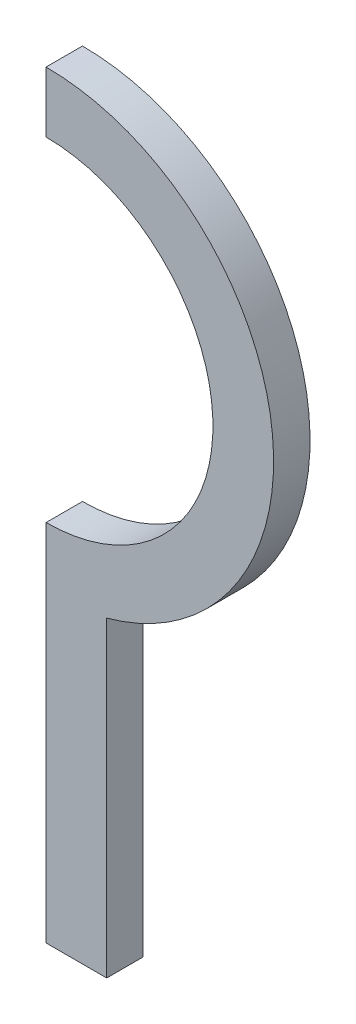
SolidWorks part; units mm, degrees
material "Balsa"
ref_plane "Front Plane" through (0, 0, 0) normal (1, 0, 0) x (0, 1, 0)
ref_plane "Top Plane" through (0, 0, 0) normal (0, 0, 1) x (0, 1, 0)
ref_plane "Right Plane" through (0, 0, 0) normal (0, 1, 0) x (-1, 0, 0)
sketch "Sketch1" plane through (0, 0, 0) normal (0, 0, 1) x (0, 1, 0)
  line L0 (25, -5) -> (26.3579, -5)
  line L1 (25, -5) -> (-25, -5)
  line L3 (25, 5) -> (-25, 5)
  line L4 (-25, -5) -> (-25, 5)
  line L5 (25, -5) -> (-25, 5) construction
  line L6 (25, 5) -> (-25, -5) construction
  line L7 (25, 5) -> (35, 5)
  line L8 (90, 5) -> (100, 5)
  arc A0 (35, 5) -> (90, 5) centre (62.5, 5) ccw
  arc A1 (26.3579, -5) -> (100, 5) centre (62.5, 5) ccw
  circle A3 centre (62.5, 5) radius 37.5 construction
  circle A4 centre (62.5, 5) radius 27.5 construction
  point P0 (0, 0)
  point P9 (88.7984, 13.0402)
  point P14 (98.3614, 15.9639)
  dimension "D3" = 55
  dimension "D5" = 10
  dimension "D1" = 10
  dimension "D2" = 50
  dimension "D4" = 10
extrude "Boss-Extrude1" add sketch "Sketch1" along normal blind 6
